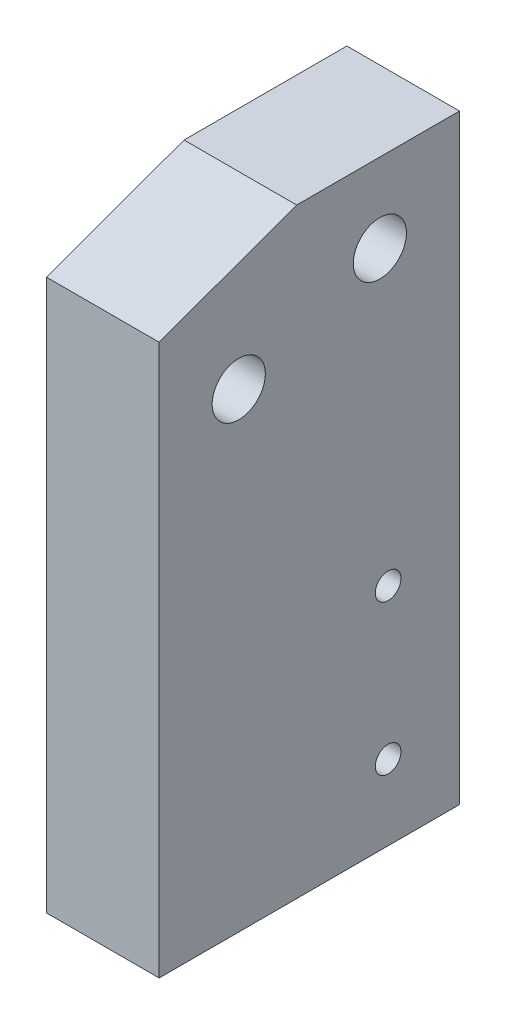
SolidWorks part; units mm, degrees
material "1060 Alloy"
ref_plane "Front Plane" through (0, 0, 0) normal (0, 0, 1) x (1, 0, 0)
ref_plane "Top Plane" through (0, 0, 0) normal (0, 1, 0) x (1, 0, 0)
ref_plane "Right Plane" through (0, 0, 0) normal (1, 0, 0) x (0, 0, -1)
sketch "Sketch1" plane through (0, 0, 0) normal (0, 1, 0) x (1, 0, 0)
  line L1 (0, 0) -> (28.575, 0)
  line L2 (0, 0) -> (0, 76.2)
  line L3 (0, 76.2) -> (28.575, 76.2)
  line L4 (28.575, 0) -> (28.575, 76.2)
  dimension "D1" = 28.575
  dimension "D2" = 76.2
extrude "Boss-Extrude1" add sketch "Sketch1" along normal blind 152.4
sketch "Sketch2" plane through (28.575, 0, 0) normal (1, 0, 0) x (0, 0, -1)
  line L0 (76.2, 139.7) -> (0, 111.9655) construction
  line L3 (76.2, 152.4) -> (76.2, 0) construction
  line L4 (0, 152.4) -> (76.2, 152.4) construction
  line L5 (0, 152.4) -> (0, 0) construction
  dimension "D2" = 20
hole_wizard "1/2 Clearance Hole1" positions "3DSketch2" profile "Sketch4" hole size "1/2" standard "ANSI Inch"
sketch3d "3DSketch2"
  line L0 (28.575, 139.7, -76.2) -> (28.575, 111.9655, 0) construction
  point P0 (28.575, 125.8327, -38.1)
  point P4 (28.575, 132.3482, -56.0011)
  point P6 (28.575, 119.3173, -20.1989)
  point P8 (28.575, 125.8327, -38.1)
  dimension "D1" = 19.05
  dimension "D2" = 19.05
sketch "Sketch4" plane through (28.575, 119.3173, -20.1989) normal (0, 1, 0) x (0, 0, -1)
  line L0 (0, 0) -> (0, 28.575)
  line L1 (0, 28.575) -> (6.7462, 28.575)
  line L2 (6.7462, 28.575) -> (6.7462, 0)
  line L5 (6.7462, 0) -> (0, 0)
  line L11 (0, -6.35) -> (0, 107.95) construction
  dimension "Thru Hole Dia." = 13.4925
  dimension "Thru Hole Depth" = 28.575
sketch "Sketch5" plane through (28.575, 0, 0) normal (1, 0, 0) x (0, 0, -1)
  line L0 (38.1, 125.8327) -> (12.5419, 196.053) construction
  line L1 (28.4303, 152.4) -> (38.1, 125.8327)
  line L2 (76.2, 139.7) -> (0, 111.9655) construction
  line L3 (38.1, 125.8327) -> (12.5419, 125.8327) construction
  line L4 (12.5419, 125.8327) -> (12.5419, 196.053) construction
  line L5 (0, 152.4) -> (76.2, 152.4) construction
  line L6 (12.5419, 125.8327) -> (12.5419, 116.5304) construction
  line L7 (12.5419, 116.5304) -> (38.1, 125.8327)
  dimension "D1" = 74.7268
ref_plane "Plane1" through (0, 98.868, 35.985) normal (0, 0.9397, 0.342) x (0, -0.342, 0.9397)
hole_wizard "Tap Drill for 5/16-18 Tap1" positions "Sketch7" profile "Sketch8" hole size "5/16-18" standard "ANSI Inch"
sketch "Sketch7" plane through (28.575, 0, 0) normal (1, 0, 0) x (0, 0, -1)
  point P0 (58.1, 57.15)
  point P2 (58.1, 19.05)
sketch "Sketch8" plane through (28.575, 57.15, -58.1) normal (0, 1, 0) x (0, 0, -1)
  line L0 (0, 0) -> (0, 14.6611)
  line L1 (0, 14.6611) -> (3.2639, 12.7)
  line L2 (3.2639, 12.7) -> (3.2639, 0)
  line L5 (3.2639, 0) -> (0, 0)
  line L10 (0, 14.6611) -> (-3.2639, 12.7) construction
  line L11 (0, -6.35) -> (0, 107.95) construction
  dimension "Hole Dia." = 6.5278
  dimension "Hole Depth" = 12.7
  dimension "Drill Angle" = 118
hole_wizard "Tap Drill for 5/16-18 Tap2" positions "Sketch9" profile "Sketch10" hole size "5/16-18" standard "ANSI Inch"
sketch "Sketch9" plane through (0, 0, 0) normal (-1, 0, 0) x (0, 0, 1)
  point P0 (-18.1, 57.15)
  point P2 (-18.1, 19.05)
sketch "Sketch10" plane through (0, 57.15, -18.1) normal (0, 1, 0) x (0, 0, 1)
  line L0 (0, 0) -> (0, 14.6611)
  line L1 (0, 14.6611) -> (3.2639, 12.7)
  line L2 (3.2639, 12.7) -> (3.2639, 0)
  line L5 (3.2639, 0) -> (0, 0)
  line L10 (0, 14.6611) -> (-3.2639, 12.7) construction
  line L11 (0, -6.35) -> (0, 107.95) construction
  dimension "Hole Dia." = 6.5278
  dimension "Hole Depth" = 12.7
  dimension "Drill Angle" = 118
sketch "Sketch12" plane through (0, 0, 0) normal (-1, 0, 0) x (0, 0, 1)
  line L0 (-34.893, 152.4) -> (0, 139.7)
  line L1 (-76.2, 152.4) -> (0, 152.4) construction
  line L2 (0, 152.4) -> (0, 0) construction
  line L3 (0, 139.7) -> (0, 152.4)
  line L4 (0, 152.4) -> (-34.893, 152.4)
  line L5 (99.9317, 75.5933) -> (-27.9617, 122.1427) construction
  point P6 (0, 0)
  point P9 (0, 0)
  dimension "D1" = 0
  dimension "D2" = 12.7
extrude "Cut-Extrude1" cut sketch "Sketch12" against normal through all
equation "\"wheel angle\"= 20"
equation "\"hole offset\"= 0.5"
equation "\"D1@Sketch2\"=\"hole offset\""
equation "\"D2@Sketch2\"=\"wheel angle\""
equation "\"hole spacing\"= 0.75"
equation "\"length\"= 8 - 2"
equation "\"D1@Boss-Extrude1\"=\"length\""
